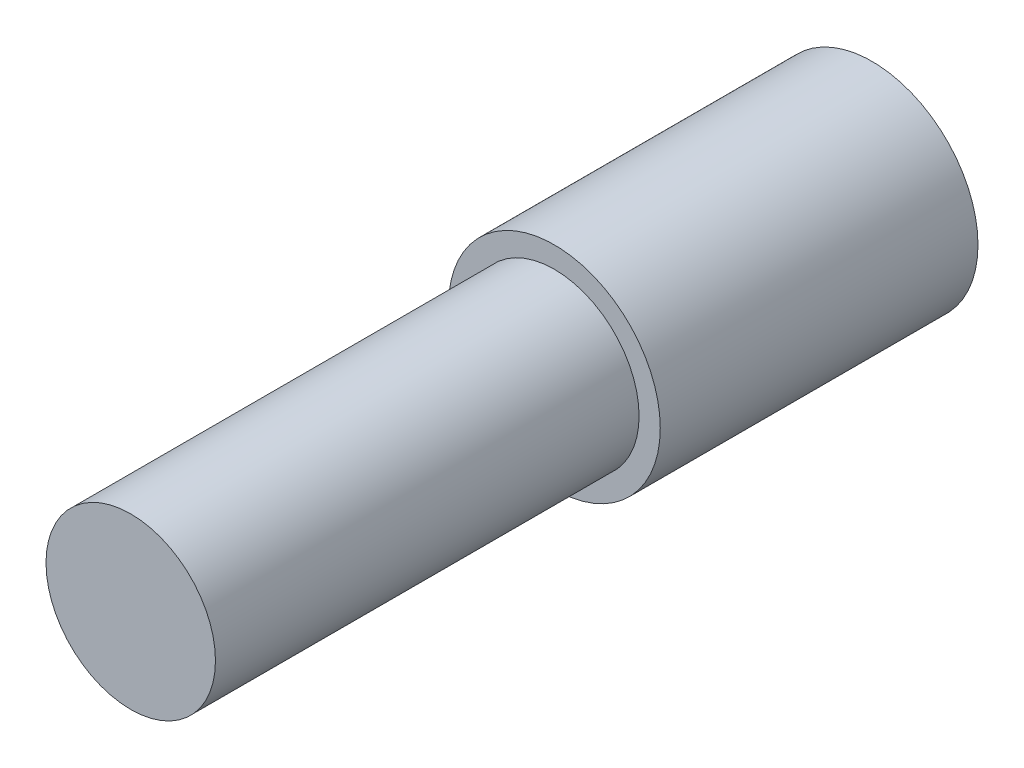
SolidWorks part; units mm, degrees
ref_plane "Front Plane" through (0, 0, 0) normal (0, 0, 1) x (1, 0, 0)
ref_plane "Top Plane" through (0, 0, 0) normal (0, 1, 0) x (1, 0, 0)
ref_plane "Right Plane" through (0, 0, 0) normal (1, 0, 0) x (0, 0, -1)
sketch "Sketch1" plane through (0, 0, 0) normal (0, 0, 1) x (1, 0, 0)
  circle A0 centre (0, 0) radius 5
  dimension "D1" = 10
extrude "Boss-Extrude1" add sketch "Sketch1" along normal blind 15
sketch "Sketch2" plane through (0, 0, 15) normal (0, 0, 1) x (1, 0, 0)
  circle A0 centre (0, 0) radius 4
  dimension "D1" = 8
extrude "Boss-Extrude2" add sketch "Sketch2" along normal blind 20
